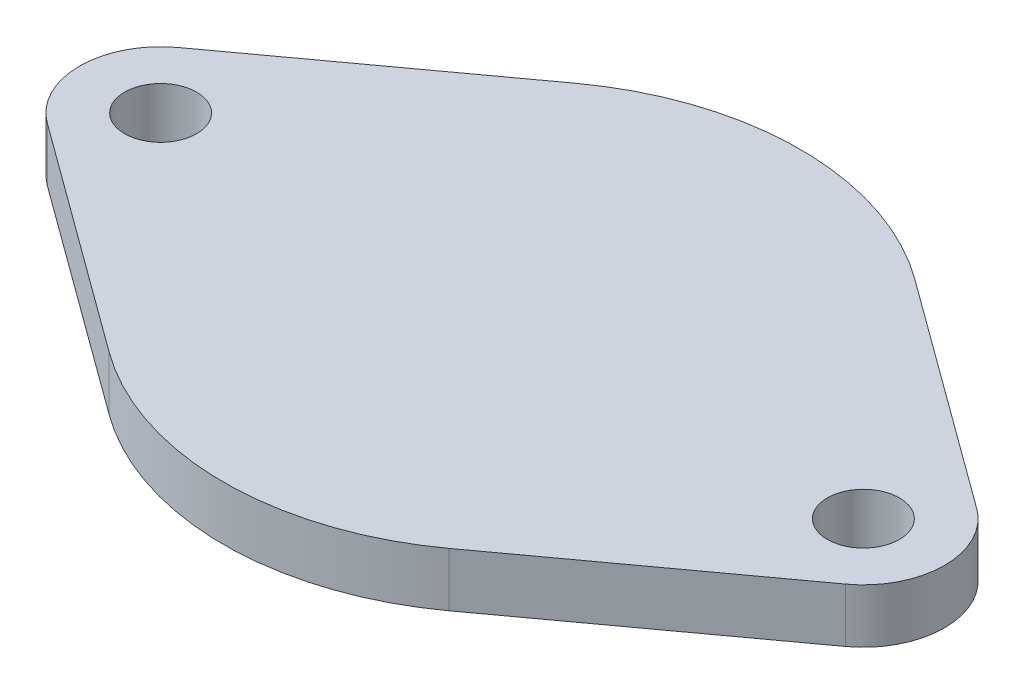
SolidWorks part; units mm, degrees
ref_plane "Спереди" through (0, 0, 0) normal (0, 0, 1) x (1, 0, 0)
ref_plane "Сверху" through (0, 0, 0) normal (0, 1, 0) x (1, 0, 0)
ref_plane "Справа" through (0, 0, 0) normal (1, 0, 0) x (0, 0, -1)
sketch "Sketch1" plane through (0, 0, 0) normal (0, 1, 0) x (1, 0, 0)
  line L0 (22.1538, -3.6342) -> (9.4359, -12.9214)
  line L1 (-9.4359, -12.9214) -> (-22.1538, -3.6342)
  line L2 (-22.1538, 3.6342) -> (-9.4359, 12.9214)
  line L3 (22.1538, 3.6342) -> (9.4359, 12.9214)
  circle A0 centre (-19.5, 0) radius 2
  circle A1 centre (19.5, 0) radius 2
  arc A2 (-9.4359, -12.9214) -> (9.4359, -12.9214) centre (0, 0) ccw
  arc A3 (-22.1538, 3.6342) -> (-22.1538, -3.6342) centre (-19.5, 0) ccw
  arc A4 (22.1538, -3.6342) -> (22.1538, 3.6342) centre (19.5, 0) ccw
  arc A5 (9.4359, 12.9214) -> (-9.4359, 12.9214) centre (0, 0) ccw
  circle A6 centre (-19.5, 0) radius 2 construction
  circle A7 centre (19.5, 0) radius 2 construction
  point P0 (0, 0)
extrude "Boss-Extrude1" add sketch "Sketch1" along normal blind 3
